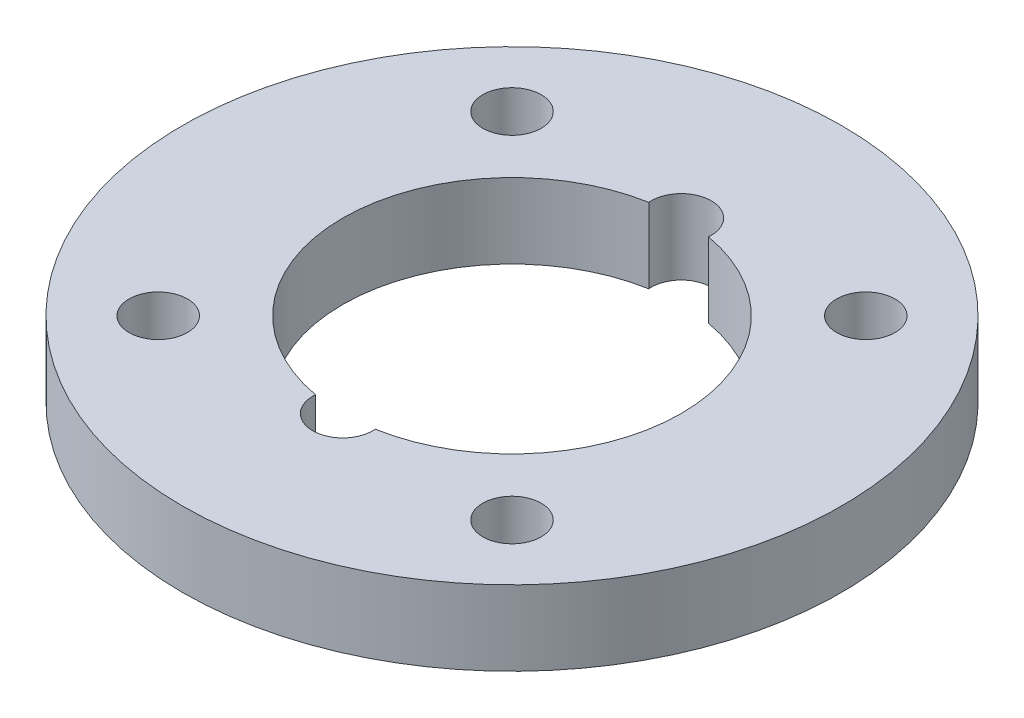
SolidWorks part; units mm, degrees
ref_plane "Front Plane" through (0, 0, 0) normal (0, 0, 1) x (1, 0, 0)
ref_plane "Top Plane" through (0, 0, 0) normal (0, 1, 0) x (1, 0, 0)
ref_plane "Right Plane" through (0, 0, 0) normal (1, 0, 0) x (0, 0, -1)
sketch "0.5in Socket" plane through (0, 0, 0) normal (0, 1, 0) x (1, 0, 0)
  line L0 (0, 0) -> (-14.997, 14.997) construction
  line L1 (14.997, -14.997) -> (0, 0) construction
  line L2 (-14.997, -14.997) -> (0, 0) construction
  line L3 (0, 0) -> (14.997, 14.997) construction
  line L4 (0, 0) -> (0, -14.351) construction
  circle A0 centre (0, 0) radius 27.94
  circle A1 centre (0, 0) radius 2.5527
  arc A2 (-2.53, 14.1262) -> (2.53, 14.1262) centre (0, 14.351) cw
  arc A3 (2.53, 14.1262) -> (2.53, -14.1262) centre (0, 0) cw
  arc A4 (2.53, -14.1262) -> (-2.53, -14.1262) centre (0, -14.351) cw
  arc A5 (-2.53, -14.1262) -> (-2.53, 14.1262) centre (0, 0) cw
  circle A6 centre (14.997, -14.997) radius 2.475
  circle A7 centre (14.997, 14.997) radius 2.475
  circle A8 centre (-14.997, 14.997) radius 2.475
  circle A9 centre (-14.997, -14.997) radius 2.475
  point P4 (0, 0)
  point P8 (0, -14.351)
  point P9 (0, 0)
  point P10 (0, 14.351)
  point P16 (0, 0)
  dimension "D1" = 55.88
  dimension "D2" = 5.1054
  dimension "D4" = 14.351
  dimension "D5" = 14.351
  dimension "D7" = 2.54
  dimension "D8" = 2.54
  dimension "D9" = 4.95
  dimension "D10" = 4.95
  dimension "D11" = 4.95
  dimension "D12" = 4.95
  dimension "D13" = 21.209
  dimension "D17" = 90
  dimension "D3" = 28.702
  dimension "D6" = 14.351
  dimension "D14" = 21.209
  dimension "D15" = 21.209
  dimension "D16" = 21.209
  dimension "D18" = 90
  dimension "D19" = 90
  dimension "D20" = 45
extrude "Boss-Extrude1" add sketch "0.5in Socket" along normal blind 6.35 contours A0 A9 A8 A7 A6 A4 A5 A2 A3
